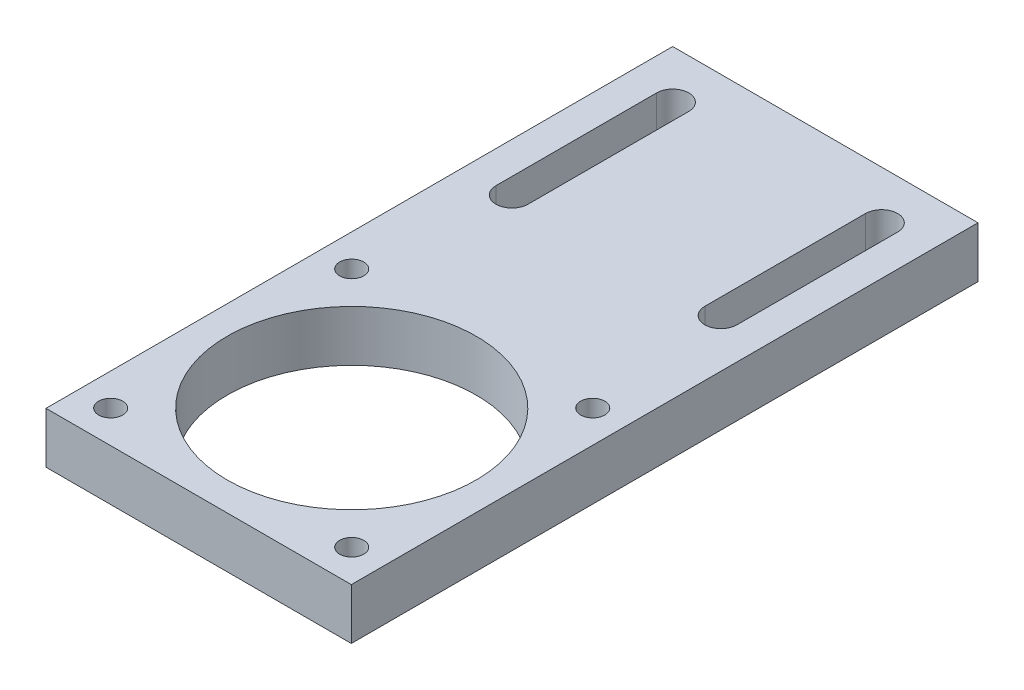
SolidWorks part; units mm, degrees
ref_plane "Front Plane" through (0, 0, 0) normal (0, 0, 1) x (1, 0, 0)
ref_plane "Top Plane" through (0, 0, 0) normal (0, 1, 0) x (1, 0, 0)
ref_plane "Right Plane" through (0, 0, 0) normal (1, 0, 0) x (0, 0, -1)
sketch "Sketch1" plane through (0, 0, 0) normal (0, 1, 0) x (1, 0, 0)
  line L0 (4, 4.05) -> (34, 4.05) construction
  line L1 (0, 0) -> (38, 0)
  line L4 (38, 0) -> (38, 78)
  line L5 (4, 34.05) -> (4, 4.05) construction
  line L7 (0, 0) -> (0, 78)
  line L9 (0, 78) -> (38, 78)
  line L10 (4, 72) -> (4, 52)
  line L11 (8, 72) -> (8, 52)
  line L12 (19, 78) -> (19, 65.6933) construction
  line L13 (30, 72) -> (30, 52)
  line L14 (34, 72) -> (34, 52)
  circle A0 centre (4, 4.05) radius 1.5
  circle A1 centre (34, 4.05) radius 1.5
  circle A2 centre (34, 34.05) radius 1.5
  circle A3 centre (4, 34.05) radius 1.5
  circle A4 centre (19, 19.05) radius 15.5
  arc A7 (8, 72) -> (4, 72) centre (6, 72) ccw
  arc A9 (4, 52) -> (8, 52) centre (6, 52) ccw
  arc A10 (34, 52) -> (30, 52) centre (32, 52) cw
  arc A11 (30, 72) -> (34, 72) centre (32, 72) cw
  point P7 (19, 4.05)
  point P8 (0, 19.05)
  point P16 (19, 0)
  point P18 (4, 19.05)
  dimension "D5" = 3
  dimension "D6" = 30
  dimension "D8" = 31
  dimension "D9" = 4
  dimension "D10" = 38
  dimension "D12" = 20
  dimension "D2" = 19.05
  dimension "D7" = 30
  dimension "D11" = 78
  dimension "D13" = 6
  dimension "D14" = 6
  dimension "D3" = 2
  dimension "D4" = 2
extrude "Boss-Extrude1" add sketch "Sketch1" along normal blind 6.35
